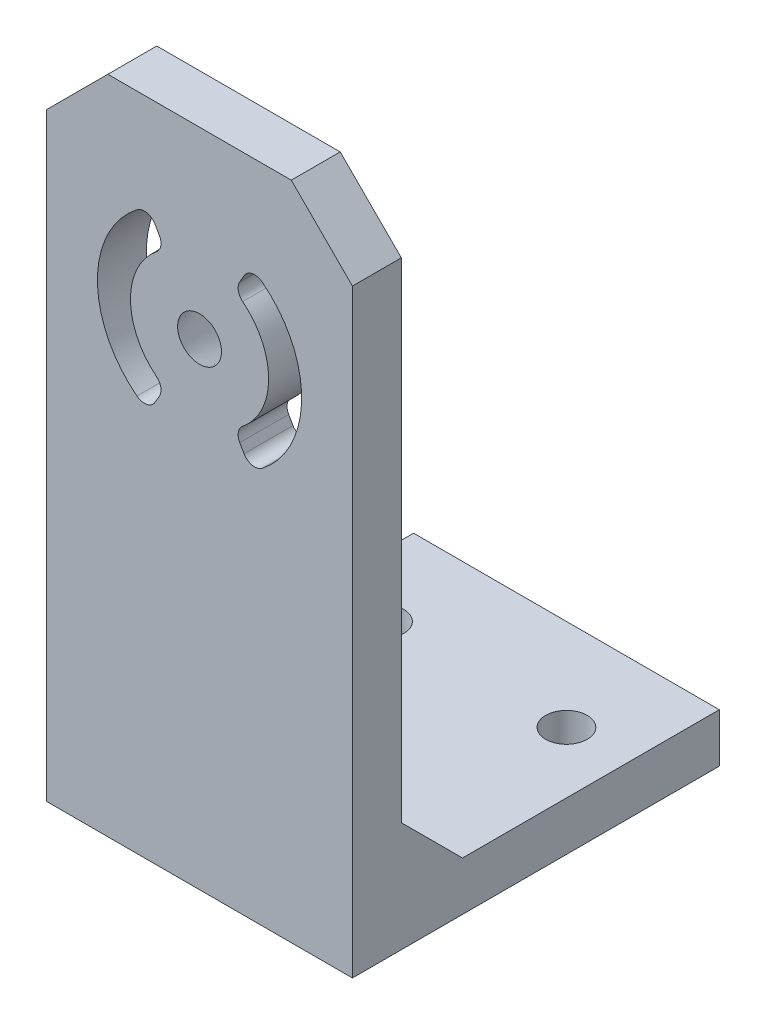
SolidWorks part; units mm, degrees
ref_plane "前视基准面" through (0, 0, 0) normal (0, 0, 1) x (1, 0, 0)
ref_plane "上视基准面" through (0, 0, 0) normal (0, 1, 0) x (1, 0, 0)
ref_plane "右视基准面" through (0, 0, 0) normal (1, 0, 0) x (0, 0, -1)
other "Configuration Table"
sketch "草图2" plane through (0, 0, 0) normal (0, 1, 0) x (1, 0, 0)
  line L1 (0, 0) -> (25, 0)
  line L2 (0, 0) -> (0, 30)
  line L3 (0, 30) -> (25, 30)
  line L4 (25, 0) -> (25, 30)
  circle A0 centre (5, 22.5) radius 1.7
  circle A1 centre (20, 22.5) radius 1.7
  point P11 (0.8549, 8.7801)
  dimension "D3" = 3.4
  dimension "D4" = 3.4
  dimension "D1" = 30
  dimension "D2" = 25
  dimension "D5" = 7.5
  dimension "D6" = 7.5
  dimension "D7" = 5
  dimension "D8" = 5
extrude "凸台-拉伸1" add sketch "草图2" along normal blind 4
sketch "草图3" plane through (0, 4, 0) normal (0, 1, 0) x (1, 0, 0)
  line L0 (25, 0) -> (25, 30) construction
  line L1 (0, 0) -> (25, 0)
  line L2 (0, 0) -> (0, 4)
  line L3 (0, 4) -> (25, 4)
  line L4 (25, 0) -> (25, 4)
  dimension "D1" = 4
extrude "凸台-拉伸2" add sketch "草图3" along normal blind 50
sketch "草图6" plane through (0, 0, -4) normal (0, 0, -1) x (-1, 0, 0)
  line L0 (-12.5, 39) -> (-16.675, 46.2313) construction
  line L1 (-25, 54) -> (0, 54) construction
  line L2 (-12.5, 54) -> (-12.5, 39) construction
  line L3 (-12.5, 39) -> (-8.325, 46.2313) construction
  line L4 (-12.5, 39) -> (-16.675, 31.7687) construction
  line L5 (-12.5, 39) -> (-8.325, 31.7687) construction
  line L6 (-16.675, 46.2313) -> (-15.325, 43.893)
  line L7 (-9.675, 43.893) -> (-8.325, 46.2313)
  line L8 (-15.325, 34.107) -> (-16.675, 31.7687)
  line L9 (-8.325, 31.7687) -> (-9.675, 34.107)
  circle A0 centre (-12.5, 39) radius 3.5 construction
  circle A1 centre (-12.5, 39) radius 8.35 construction
  circle A2 centre (-12.5, 39) radius 5.65 construction
  arc A3 (-15.325, 43.893) -> (-15.325, 34.107) centre (-12.5, 39) ccw
  arc A4 (-16.675, 46.2313) -> (-16.675, 31.7687) centre (-12.5, 39) ccw
  arc A5 (-8.325, 46.2313) -> (-8.325, 31.7687) centre (-12.5, 39) cw
  arc A6 (-9.675, 43.893) -> (-9.675, 34.107) centre (-12.5, 39) cw
  dimension "D2" = 7
  dimension "D3" = 11.3
  dimension "D4" = 16.7
  dimension "D1" = 15
  dimension "D5" = 30
  dimension "D6" = 30
  dimension "D7" = 150
  dimension "D8" = 150
sketch "草图7" plane through (0, 0, -4) normal (0, 0, -1) x (-1, 0, 0)
  line L0 (-25, 54) -> (-25, 4) construction
  line L1 (-25, 54) -> (0, 54) construction
  circle A1 centre (-12.5, 39) radius 3.25
  point P7 (-9.655, 48.1946)
  dimension "D1" = 6.5
  dimension "D2" = 12.5
  dimension "D3" = 15
extrude "切除-拉伸3" cut sketch "草图7" against normal blind 4 draft 20
extrude "切除-拉伸4" cut sketch "草图6" against normal through all
sketch "草图9" plane through (0, 0, 0) normal (-1, 0, 0) x (0, 0, 1)
  line L0 (-9, 4) -> (-4, 4)
  line L1 (-30, 4) -> (-4, 4) construction
  line L2 (-4, 4) -> (-4, 9)
  line L3 (-4, 54) -> (-4, 4) construction
  line L4 (-4, 9) -> (-9, 4)
  dimension "D1" = 5
  dimension "D2" = 5
extrude "凸台-拉伸3" add sketch "草图9" against normal up to surface (25 mm away) up to face at (25, 19.3333, -11.3333)
chamfer "倒角1" distance 5 angle 45 2 edges at (25, 54, -2) (0, 54, -2)
fillet "圆角1" radius 1 8 edges at (8.325, 46.2313, -2) (9.675, 43.893, -2) (8.325, 31.7687, -2) (9.675, 34.107, -2) (16.675, 31.7687, -2) (15.325, 34.107, -2) (16.675, 46.2313, -2) (15.325, 43.893, -2)
